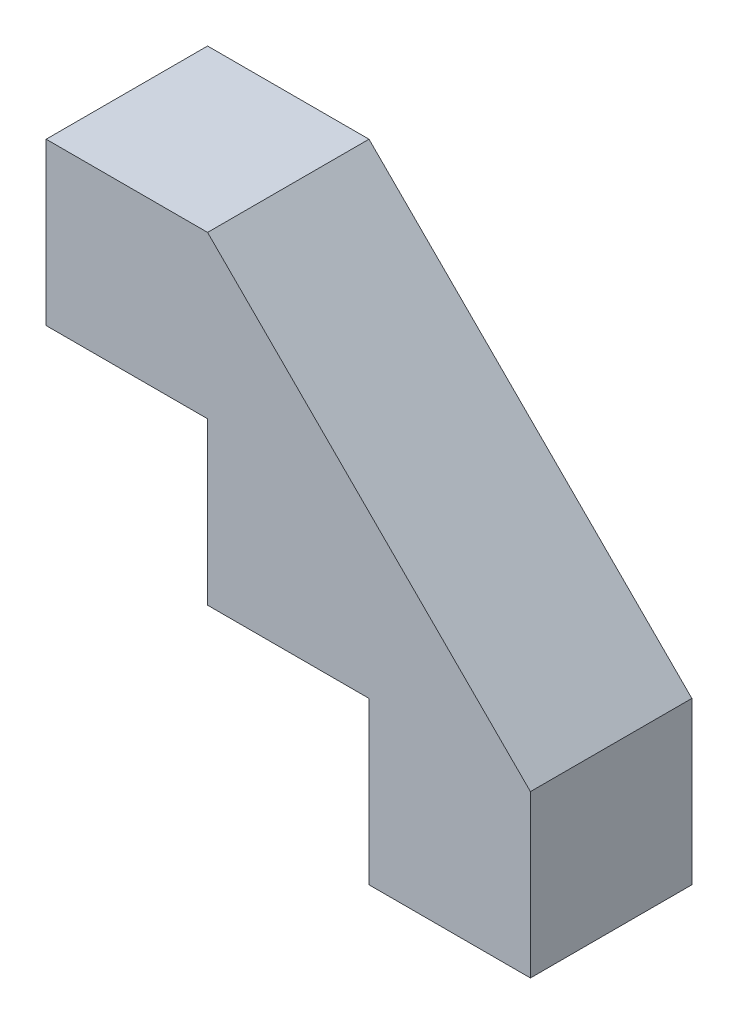
SolidWorks part; units mm, degrees
ref_plane "Front Plane" through (0, 0, 0) normal (0, 0, 1) x (1, 0, 0)
ref_plane "Top Plane" through (0, 0, 0) normal (0, 1, 0) x (1, 0, 0)
ref_plane "Right Plane" through (0, 0, 0) normal (1, 0, 0) x (0, 0, -1)
sketch "Sketch1" plane through (0, 0, 0) normal (0, 0, 1) x (1, 0, 0)
  line L0 (0, 0) -> (0, 3)
  line L1 (0, 6) -> (6, 0)
  line L2 (0, 0) -> (3, 0)
  line L3 (6, 0) -> (6, -3)
  line L4 (6, -3) -> (3, -3)
  line L5 (3, -3) -> (3, 0)
  line L6 (0, 6) -> (-3, 6)
  line L7 (-3, 6) -> (-3, 3)
  line L8 (-3, 3) -> (0, 3)
  dimension "D1" = 6
  dimension "D2" = 6
  dimension "D3" = 3
  dimension "D5" = 3
  dimension "D6" = 3
extrude "Boss-Extrude1" add sketch "Sketch1" along normal blind 3
